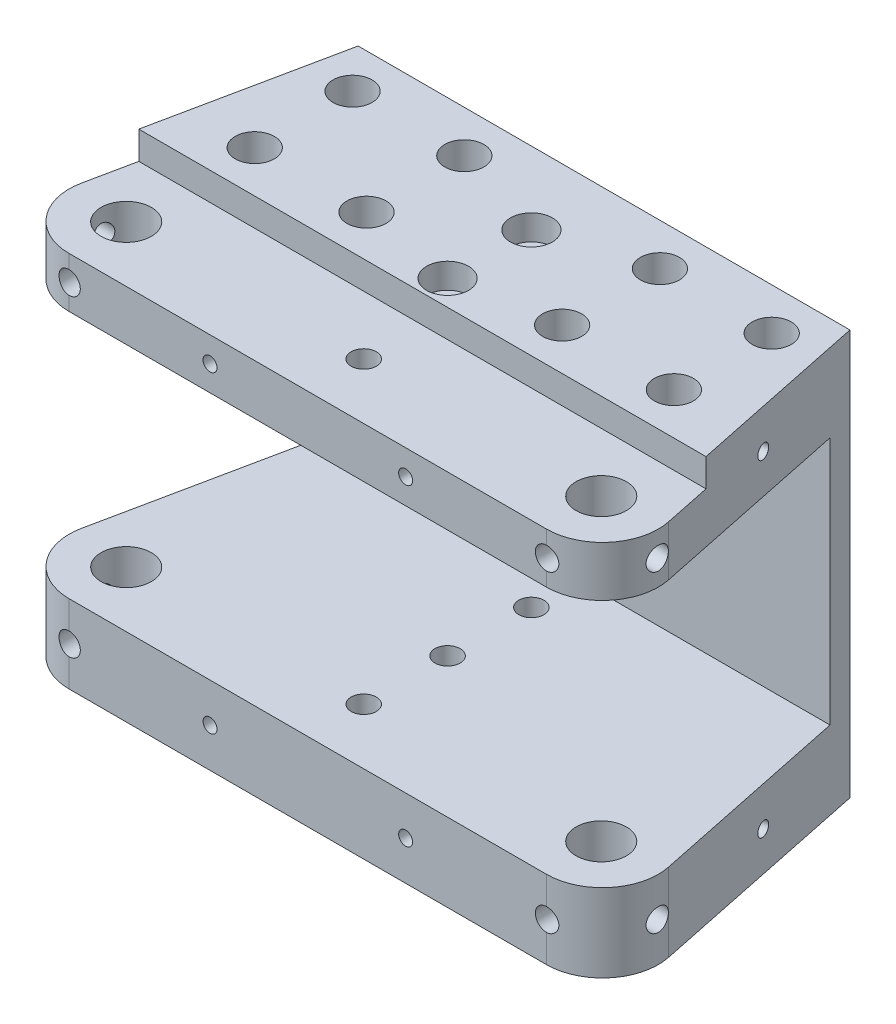
SolidWorks part; units mm, degrees
ref_plane "前视基准面" through (0, 0, 0) normal (0, 0, 1) x (1, 0, 0)
ref_plane "上视基准面" through (0, 0, 0) normal (0, 1, 0) x (1, 0, 0)
ref_plane "右视基准面" through (0, 0, 0) normal (1, 0, 0) x (0, 0, -1)
sketch "草图1" plane through (0, 0, 0) normal (0, 0, 1) x (1, 0, 0)
  line L1 (0, 0) -> (220, 0)
  line L2 (0, 0) -> (0, -145)
  line L3 (0, -145) -> (220, -145)
  line L4 (220, 0) -> (220, -145)
  dimension "D1" = 220
  dimension "D2" = 145
extrude "拉伸1" add sketch "草图1" along normal blind 9
sketch "草图9" plane through (0, 0, 0) normal (0, 0, -1) x (-1, 0, 0)
  line L0 (0, 0) -> (0, -145) construction
  line L2 (-220, 0) -> (0, 0) construction
  circle A0 centre (-110, -72.5) radius 22.5
  dimension "D1" = 72.5
  dimension "D2" = 45
  dimension "D3" = 110
extrude "切除-拉伸4" cut sketch "草图9" against normal blind 430
sketch "草图11" plane through (0, 0, 9) normal (0, 0, 1) x (1, 0, 0)
  line L0 (220, -145) -> (220, 0) construction
  line L1 (0, -145) -> (220, -145)
  line L2 (0, -145) -> (0, -117)
  line L3 (0, -117) -> (220, -117)
  line L4 (220, -145) -> (220, -117)
  line L6 (0, 0) -> (220, 0)
  line L7 (0, 0) -> (0, -28)
  line L8 (0, -28) -> (220, -28)
  line L9 (220, 0) -> (220, -28)
  dimension "D1" = 28
  dimension "D2" = 28
extrude "拉伸3" add sketch "草图11" along normal blind 97
sketch "草图12" plane through (0, -145, 0) normal (0, -1, 0) x (1, 0, 0)
  line L0 (0, 106) -> (0, 0) construction
  line L1 (0, 106) -> (220, 106) construction
  line L2 (220, 106) -> (220, 0) construction
  circle A0 centre (25, 86) radius 9
  circle A1 centre (195, 86) radius 9
  dimension "D1" = 18
  dimension "D2" = 25
  dimension "D3" = 20
  dimension "D4" = 25
  dimension "D5" = 20
  dimension "D6" = 18
extrude "切除-拉伸6" cut sketch "草图12" against normal through all
sketch "草图13" plane through (0, 0, 0) normal (0, 0, -1) x (-1, 0, 0)
  line L0 (-167, -129.5) -> (-53, -129.5) construction
  line L1 (-167, -129.5) -> (-167, -15.5) construction
  circle A0 centre (-167, -129.5) radius 6
  circle A1 centre (-53, -129.5) radius 6
  circle A2 centre (-167, -15.5) radius 6
  circle A3 centre (-53, -15.5) radius 6
  circle A4 centre (-110, -72.5) radius 22.5 construction
  dimension "D2" = 57
  dimension "D3" = 57
  dimension "D1" = 90
extrude "切除-拉伸9" cut sketch "草图13" against normal blind 20
sketch "草图15" plane through (0, 0, 0) normal (0, 1, 0) x (1, 0, 0)
  line L0 (0, -106) -> (0, 0) construction
  line L1 (220, -106) -> (0, -106)
  line L2 (220, -106) -> (220, -65)
  line L3 (220, -65) -> (0, -65)
  line L4 (0, -106) -> (0, -65)
  dimension "D1" = 41
extrude "切除-拉伸10" cut sketch "草图15" against normal blind 10
sketch "草图16" plane through (0, -145, 0) normal (0, -1, 0) x (1, 0, 0)
  line L0 (0, 106) -> (22, 0)
  line L1 (0, 0) -> (220, 0) construction
  line L2 (22, 0) -> (0, 0)
  line L3 (220, 106) -> (198, 0)
  line L4 (198, 0) -> (220, 0)
  line L5 (220, 0) -> (220, 106)
  line M3 (0, 0) -> (220, 0)
  line M4 (220, 0) -> (220, 106)
  line M6 (0, 106) -> (0, 0)
  dimension "D1" = 22
  dimension "D2" = 22
extrude "切除-拉伸11" cut sketch "草图16" against normal through all contours L0 M6 M3 | L3 M4 M3
fillet "圆角1" radius 20 4 edges at (0, -19, 106) (220, -19, 106) (220, -131, 106) (0, -131, 106)
sketch "草图18" plane through (0, 0, 106) normal (0, 0, 1) x (1, 0, 0)
  line L0 (24.5772, -117) -> (24.5772, -145) construction
  line L1 (24.5772, -10) -> (24.5772, -28) construction
  line L2 (195.4228, -145) -> (195.4228, -117) construction
  line L3 (195.4228, -28) -> (195.4228, -10) construction
  circle A0 centre (24.5772, -131) radius 4
  circle A1 centre (24.5772, -19) radius 4
  circle A2 centre (195.4228, -131) radius 4
  circle A3 centre (195.4228, -19) radius 4
  dimension "D1" = 8
  dimension "D2" = 8
extrude "切除-拉伸13" cut sketch "草图18" against normal blind 20
sketch "草图22" plane through (0, 0, 0) normal (0, 1, 0) x (1, 0, 0)
  line L0 (185, -50) -> (145, -50) construction
  line L1 (185, -50) -> (185, -15) construction
  line L4 (35, -50) -> (35, -15) construction
  line L5 (35, -50) -> (75, -50) construction
  circle A0 centre (145, -50) radius 7
  circle A1 centre (75, -15) radius 7
  circle A2 centre (35, -50) radius 7
  circle A3 centre (35, -15) radius 7
  circle A4 centre (185, -15) radius 7
  circle A5 centre (185, -50) radius 7
  circle A6 centre (145, -15) radius 7
  circle A7 centre (75, -50) radius 7
  circle A10 centre (105, -50) radius 7 [skipped]
  circle A11 centre (65, -50) radius 7 [skipped]
  circle A12 centre (25, -50) radius 7 [skipped]
  circle A13 centre (105, -15) radius 7 [skipped]
  circle A14 centre (65, -15) radius 7 [skipped]
  circle A15 centre (25, -15) radius 7 [skipped]
  dimension "D5" = 40
  dimension "D2" = 40
  dimension "D3" = 13
  dimension "D4" = 13
  dimension "D1" = 90
extrude "切除-拉伸26" cut sketch "草图22" against normal blind 25
sketch "草图23" plane through (0, -145, 0) normal (0, -1, 0) x (1, 0, 0)
  circle A0 centre (35, 50) radius 7
  circle A1 centre (75, 50) radius 7
  circle A2 centre (75, 15) radius 7
  circle A3 centre (35, 15) radius 7
  circle A4 centre (145, 15) radius 7
  circle A5 centre (145, 50) radius 7
  circle A6 centre (185, 50) radius 7
  circle A7 centre (185, 15) radius 7
extrude "切除-拉伸27" cut sketch "草图23" against normal blind 25
sketch "草图26" plane through (0, -145, 0) normal (0, -1, 0) x (1, 0, 0)
  circle A0 centre (110, 86) radius 4.5
  circle A1 centre (110, 56) radius 4.5
  circle A2 centre (110, 26) radius 4.5
  dimension "D3" = 9
extrude "切除-拉伸29" cut sketch "草图26" against normal through all
sketch "草图27" plane through (0, 0, 0) normal (0, 1, 0) x (1, 0, 0)
  circle A0 centre (110, -26) radius 7.5
  circle A1 centre (110, -56) radius 7.5
extrude "切除-拉伸30" cut sketch "草图27" against normal blind 9
sketch "草图28" plane through (0, -145, 0) normal (0, -1, 0) x (1, 0, 0)
  circle A0 centre (110, 86) radius 7.5
  circle A1 centre (110, 56) radius 7.5
  circle A2 centre (110, 26) radius 7.5
extrude "切除-拉伸31" cut sketch "草图28" against normal blind 9
sketch "草图29" plane through (0, 0, 0) normal (1, 0, 0) x (0, 0, -1)
  line L0 (-106, -15) -> (-106, -10) construction
  line L2 (-106, -127) -> (-106, -117) construction
  line L3 (-81.9357, -117) -> (-9, -117) construction
  circle A0 centre (-86, -19) radius 4
  circle A1 centre (-86, -131) radius 4
  dimension "D2" = 20
  dimension "D1" = 20
  dimension "D3" = 14
extrude "切除-拉伸32" cut sketch "草图29" along normal blind 29
pattern_linear "阵列(线性)1" count 2 spacing 200 along (1, 0, 0) of "切除-拉伸32"
sketch "草图30" plane through (0, 0, 106) normal (0, 0, 1) x (1, 0, 0)
  line L0 (24.5772, -10) -> (24.5772, -15) construction
  circle A0 centre (75, -19) radius 2.5
  circle A1 centre (145, -19) radius 2.5
  circle A2 centre (75, -131) radius 2.5
  circle A3 centre (145, -131) radius 2.5
  dimension "D1" = 50.4228
  dimension "D2" = 70
extrude "切除-拉伸33" cut sketch "草图30" against normal blind 10
sketch "草图31" plane through (21.0915, 0, 4.3775) normal (-0.9791, 0, -0.2032) x (-0.2032, 0, 0.9791)
  circle A0 centre (35.5292, -131) radius 2.5
  circle A1 centre (35.5292, -14) radius 2.5
extrude "切除-拉伸34" cut sketch "草图31" against normal blind 10
sketch "草图32" plane through (189.8232, 0, -39.3973) normal (0.9791, 0, -0.2032) x (-0.2032, 0, -0.9791)
  circle A0 centre (-80.2369, -131) radius 2.5
  circle A1 centre (-80.2369, -14) radius 2.5
extrude "切除-拉伸35" cut sketch "草图32" against normal blind 10
